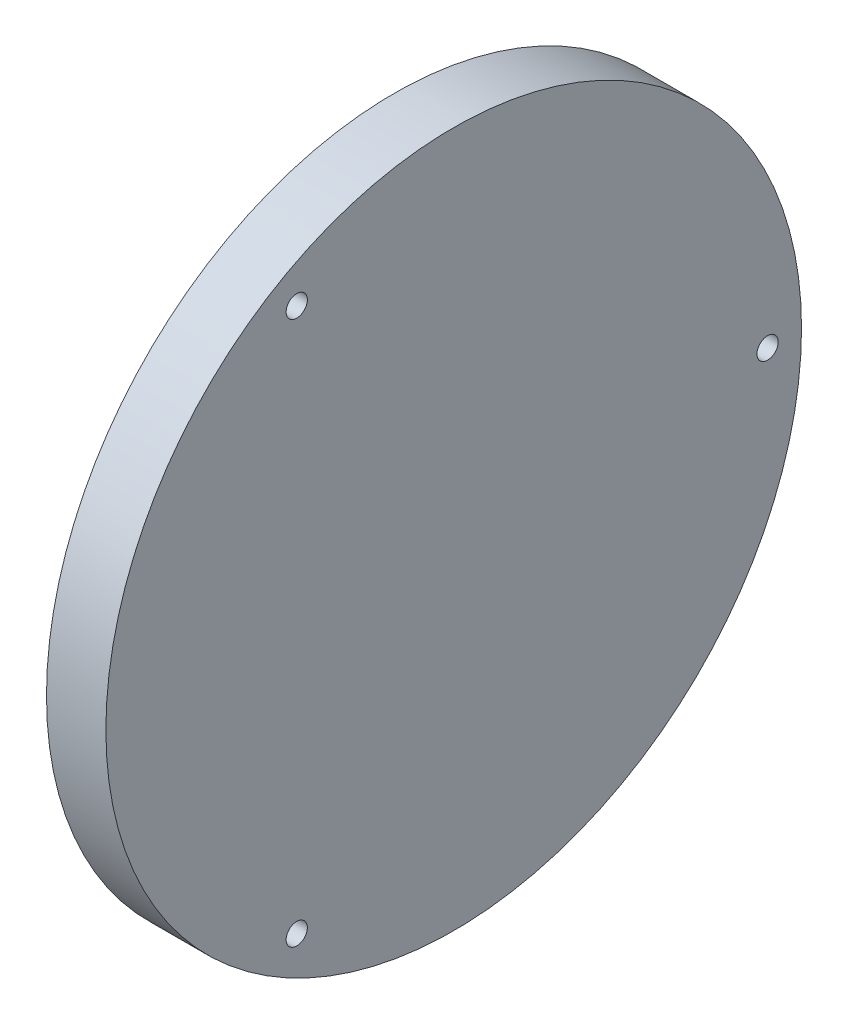
SolidWorks part; units mm, degrees
ref_plane "Front Plane" through (0, 0, 0) normal (0, 0, 1) x (1, 0, 0)
ref_plane "Top Plane" through (0, 0, 0) normal (0, 1, 0) x (1, 0, 0)
ref_plane "Right Plane" through (0, 0, 0) normal (1, 0, 0) x (0, 0, -1)
sketch "Axial blank profile" plane through (0, 0, 0) normal (0, 0, 1) x (1, 0, 0)
  line L0 (-60, 0) -> (30, 0) construction
  line L1 (0, 0) -> (7, 0)
  line L2 (7, 0) -> (7, 41)
  line L3 (7, 41) -> (0, 41)
  line L4 (0, 41) -> (0, 29)
  line L5 (0, 29) -> (4, 29)
  line L6 (4, 29) -> (4, 10)
  line L7 (4, 10) -> (0, 10)
  line L8 (0, 10) -> (0, 0)
revolve "Native revolved blank" add sketch "Axial blank profile" angle 360 about L0
sketch "Six integral dry magnet-well islands sketch" plane through (0, 0, 0) normal (1, 0, 0) x (0, 0, -1)
  circle A0 centre (0, 20) radius 7.5
  circle A1 centre (-17.3205, 10) radius 7.5
  circle A2 centre (-17.3205, -10) radius 7.5
  circle A3 centre (0, -20) radius 7.5
  circle A4 centre (17.3205, -10) radius 7.5
  circle A5 centre (17.3205, 10) radius 7.5
extrude "Six integral dry magnet-well islands" add sketch "Six integral dry magnet-well islands sketch" along normal blind 4 from offset 0
sketch "Integral 6mm-wide channel divider sketch" plane through (0, 0, 0) normal (1, 0, 0) x (0, 0, -1)
  line L0 (3, 9) -> (3, 30)
  line L1 (3, 30) -> (-3, 30)
  line L2 (-3, 30) -> (-3, 9)
  line L3 (-3, 9) -> (3, 9)
extrude "Integral 6mm-wide channel divider" add sketch "Integral 6mm-wide channel divider sketch" along normal blind 4 from offset 0
sketch "Seven dry blind magnet wells depth4p5 sketch" plane through (0, 0, 0) normal (1, 0, 0) x (0, 0, -1)
  circle A0 centre (0, 0) radius 6.15
  circle A1 centre (0, 20) radius 4.15
  circle A2 centre (-17.3205, 10) radius 4.15
  circle A3 centre (-17.3205, -10) radius 4.15
  circle A4 centre (0, -20) radius 4.15
  circle A5 centre (17.3205, -10) radius 4.15
  circle A6 centre (17.3205, 10) radius 4.15
extrude "Seven dry blind magnet wells depth4p5" cut sketch "Seven dry blind magnet wells depth4p5 sketch" along normal blind 4.5 from offset 0
sketch "Center-well ID14x1p5 face gland sketch" plane through (0, 0, 0) normal (1, 0, 0) x (0, 0, -1)
  circle A0 centre (0, 0) radius 6.75
  circle A1 centre (0, 0) radius 8.75
extrude "Center-well ID14x1p5 face gland" cut sketch "Center-well ID14x1p5 face gland sketch" along normal blind 1.15 from offset 0
sketch "Outer dry-well face gland 1 sketch" plane through (0, 0, 0) normal (1, 0, 0) x (0, 0, -1)
  circle A0 centre (0, 20) radius 4.75
  circle A1 centre (0, 20) radius 6.75
extrude "Outer dry-well face gland 1" cut sketch "Outer dry-well face gland 1 sketch" along normal blind 1.15 from offset 0
sketch "Outer dry-well face gland 2 sketch" plane through (0, 0, 0) normal (1, 0, 0) x (0, 0, -1)
  circle A0 centre (-17.3205, 10) radius 4.75
  circle A1 centre (-17.3205, 10) radius 6.75
extrude "Outer dry-well face gland 2" cut sketch "Outer dry-well face gland 2 sketch" along normal blind 1.15 from offset 0
sketch "Outer dry-well face gland 3 sketch" plane through (0, 0, 0) normal (1, 0, 0) x (0, 0, -1)
  circle A0 centre (-17.3205, -10) radius 4.75
  circle A1 centre (-17.3205, -10) radius 6.75
extrude "Outer dry-well face gland 3" cut sketch "Outer dry-well face gland 3 sketch" along normal blind 1.15 from offset 0
sketch "Outer dry-well face gland 4 sketch" plane through (0, 0, 0) normal (1, 0, 0) x (0, 0, -1)
  circle A0 centre (0, -20) radius 4.75
  circle A1 centre (0, -20) radius 6.75
extrude "Outer dry-well face gland 4" cut sketch "Outer dry-well face gland 4 sketch" along normal blind 1.15 from offset 0
sketch "Outer dry-well face gland 5 sketch" plane through (0, 0, 0) normal (1, 0, 0) x (0, 0, -1)
  circle A0 centre (17.3205, -10) radius 4.75
  circle A1 centre (17.3205, -10) radius 6.75
extrude "Outer dry-well face gland 5" cut sketch "Outer dry-well face gland 5 sketch" along normal blind 1.15 from offset 0
sketch "Outer dry-well face gland 6 sketch" plane through (0, 0, 0) normal (1, 0, 0) x (0, 0, -1)
  circle A0 centre (17.3205, 10) radius 4.75
  circle A1 centre (17.3205, 10) radius 6.75
extrude "Outer dry-well face gland 6" cut sketch "Outer dry-well face gland 6 sketch" along normal blind 1.15 from offset 0
sketch "Perimeter ID62x2 face gland sketch" plane through (0, 0, 0) normal (1, 0, 0) x (0, 0, -1)
  circle A0 centre (0, 0) radius 30.7
  circle A1 centre (0, 0) radius 33.3
extrude "Perimeter ID62x2 face gland" cut sketch "Perimeter ID62x2 face gland sketch" along normal blind 1.5 from offset 0
sketch "Six rear M3 pilot pockets PCD74 sketch" plane through (0, 0, 0) normal (1, 0, 0) x (0, 0, -1)
  circle A0 centre (0, 37) radius 1.25
  circle A1 centre (-32.0429, 18.5) radius 1.25
  circle A2 centre (-32.0429, -18.5) radius 1.25
  circle A3 centre (0, -37) radius 1.25
  circle A4 centre (32.0429, -18.5) radius 1.25
  circle A5 centre (32.0429, 18.5) radius 1.25
extrude "Six rear M3 pilot pockets PCD74" cut sketch "Six rear M3 pilot pockets PCD74 sketch" along normal blind 4 from offset 0
sketch "Three independent target-clamp pilots PCD74 sketch" plane through (0, 0, 0) normal (1, 0, 0) x (0, 0, -1)
  circle A0 centre (-18.5, 32.0429) radius 1.25
  circle A1 centre (-18.5, -32.0429) radius 1.25
  circle A2 centre (37, 0) radius 1.25
extrude "Three independent target-clamp pilots PCD74" cut sketch "Three independent target-clamp pilots PCD74 sketch" along normal blind 3 from offset 4
